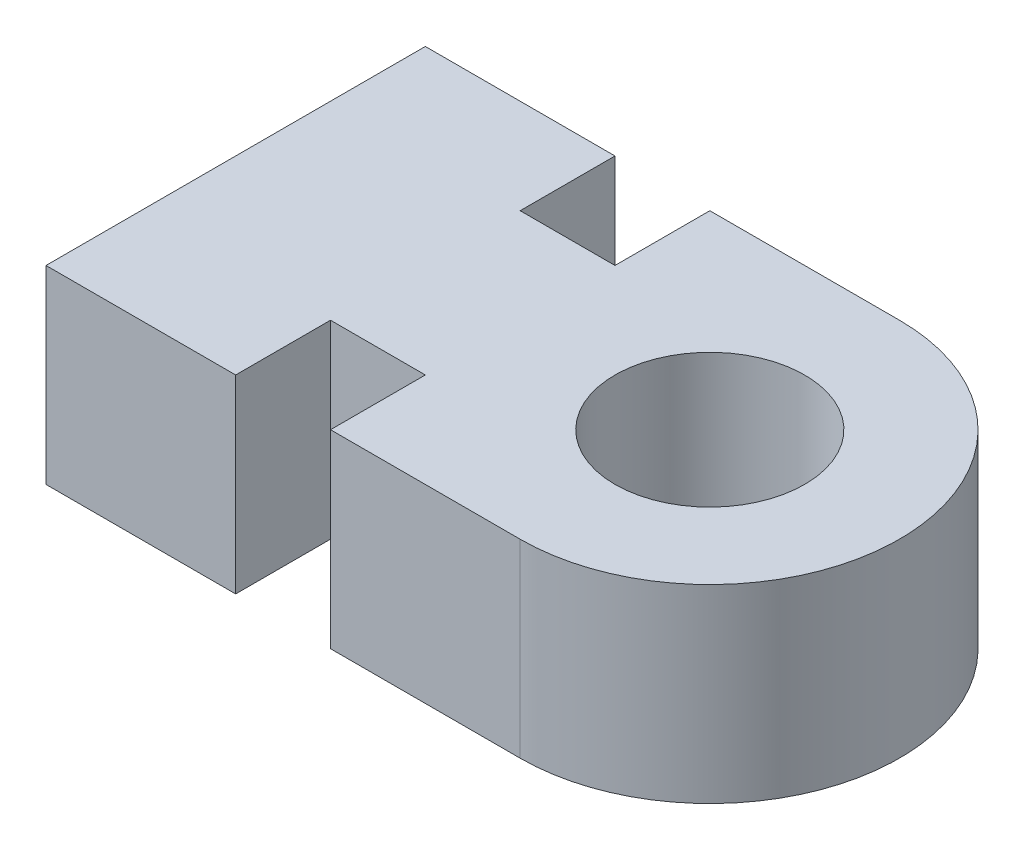
SolidWorks part; units mm, degrees
ref_plane "前基準面" through (0, 0, 0) normal (0, 0, 1) x (1, 0, 0)
ref_plane "上基準面" through (0, 0, 0) normal (0, 1, 0) x (1, 0, 0)
ref_plane "右基準面" through (0, 0, 0) normal (1, 0, 0) x (0, 0, -1)
sketch "草圖1" plane through (0, 0, 0) normal (0, 1, 0) x (1, 0, 0)
  line L0 (0, 10) -> (0, -10) construction
  line L1 (0, 10) -> (-10, 10)
  line L2 (-10, 10) -> (-10, 5)
  line L3 (-10, 5) -> (-15, 5)
  line L4 (-15, 5) -> (-15, 10)
  line L5 (-15, 10) -> (-25, 10)
  line L6 (-25, 10) -> (-25, -10)
  line L7 (-25, 0) -> (0, 0) construction
  line L8 (-15, -10) -> (-25, -10)
  line L9 (-15, -5) -> (-15, -10)
  line L10 (-10, -10) -> (-10, -5)
  line L11 (-10, -5) -> (-15, -5)
  line L12 (0, -10) -> (-10, -10)
  arc A0 (0, -10) -> (0, 10) centre (0, 0) ccw
  circle A1 centre (0, 0) radius 5
  dimension "D1" = 20
  dimension "D7" = 10
  dimension "D2" = 5
  dimension "D3" = 10
  dimension "D4" = 5
  dimension "D5" = 10
  dimension "D6" = 10
extrude "填料-伸長1" add sketch "草圖1" along normal blind 10
